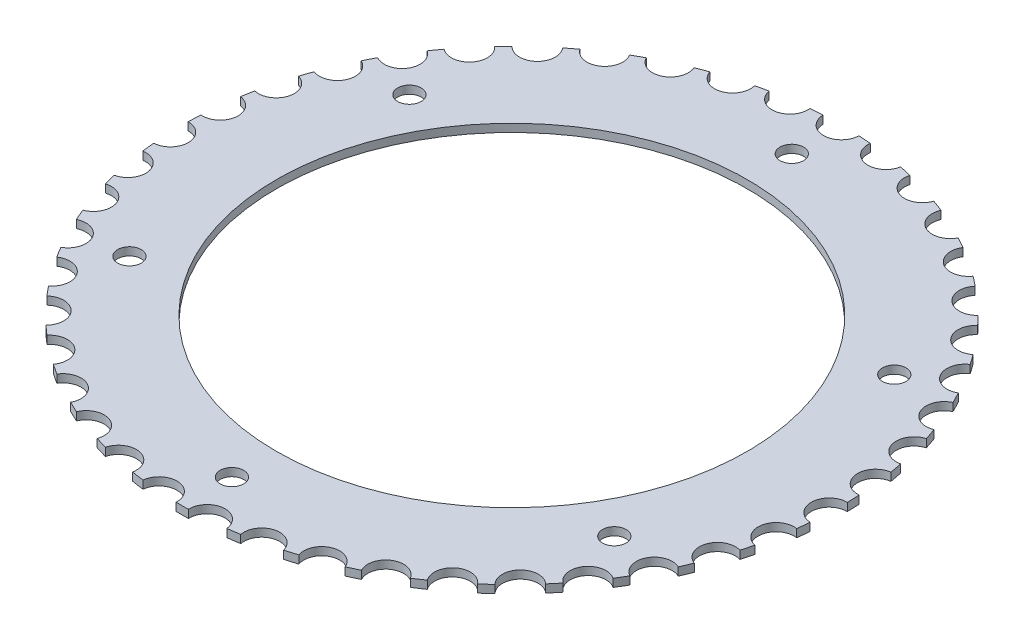
SolidWorks part; units mm, degrees
ref_plane "Front Plane" through (0, 0, 0) normal (0, 0, 1) x (1, 0, 0)
ref_plane "Top Plane" through (0, 0, 0) normal (0, 1, 0) x (1, 0, 0)
ref_plane "Right Plane" through (0, 0, 0) normal (1, 0, 0) x (0, 0, -1)
sketch "Sketch1" plane through (0, 0, 0) normal (0, 1, 0) x (1, 0, 0)
  circle A0 centre (0, 0) radius 70
  circle A1 centre (0, 0) radius 50
  dimension "D1" = 140
extrude "Boss-Extrude1" add sketch "Sketch1" along normal blind 1.7
sketch "Sketch3" plane through (0, 1.7, 0) normal (0, 1, 0) x (1, 0, 0)
  line L0 (0, 0) -> (0, 70) construction
  circle A0 centre (0, 70) radius 3.81
  circle A1 centre (0, 0) radius 70 construction
extrude "Cut-Extrude1" cut sketch "Sketch3" against normal blind 2.54
sketch "Sketch4" plane through (0, 0, 0) normal (0, 1, 0) x (1, 0, 0)
  point P0 (0, 0)
pattern_circular "CirPattern1" count 43 over 360 about axis through (0, 0, 0) along (0, 1, 0) of "Cut-Extrude1"
sketch "Sketch5" plane through (0, 0, 0) normal (0, -1, 0) x (-1, 0, 0)
  circle A0 centre (0, 0) radius 59.45 construction
  circle A1 centre (0, 59.45) radius 2.5
  circle A2 centre (51.4852, 29.725) radius 2.5
  circle A3 centre (51.4852, -29.725) radius 2.5
  circle A4 centre (0, -59.45) radius 2.5
  circle A5 centre (-51.4852, -29.725) radius 2.5
  circle A6 centre (-51.4852, 29.725) radius 2.5
  point P17 (0, 0)
  dimension "D1" = 5
  dimension "D2" = 6
extrude "Cut-Extrude2" cut sketch "Sketch5" against normal blind 10
